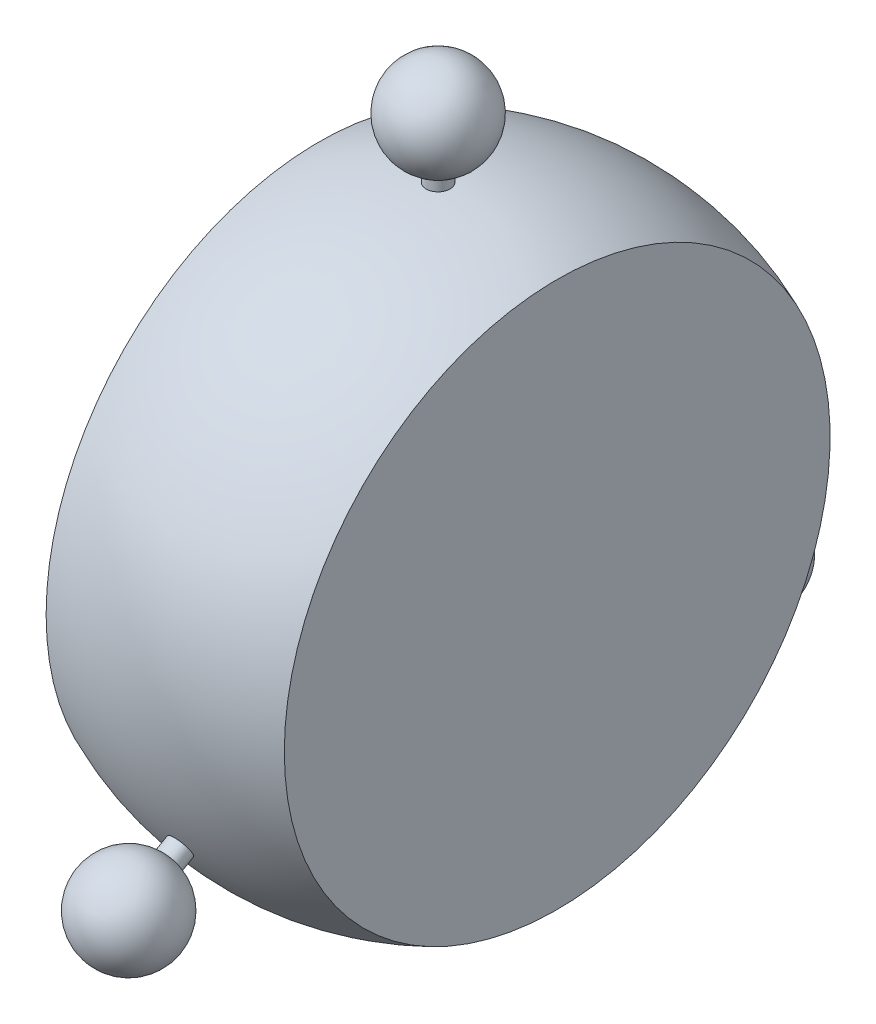
SolidWorks part; units mm, degrees
ref_plane "Alzado" through (0, 0, 0) normal (0, 0, 1) x (1, 0, 0)
ref_plane "Planta" through (0, 0, 0) normal (0, 1, 0) x (1, 0, 0)
ref_plane "Vista lateral" through (0, 0, 0) normal (1, 0, 0) x (0, 0, -1)
sketch "Croquis1" plane through (0, 0, 0) normal (0, 0, 1) x (1, 0, 0)
  line L0 (0, -25) -> (0, -20)
  line L1 (0, 20) -> (0, 25)
  line L2 (0, 0) -> (0, 16.1824) construction
  arc A0 (0, -20) -> (0, 20) centre (0, 0) ccw
  arc A1 (0, -25) -> (0, 25) centre (0, 0) ccw
  dimension "D1" = 20
  dimension "D2" = 25
sketch "Croquis2" plane through (0, 0, 0) normal (0, 1, 0) x (1, 0, 0)
  line L15 (-10, -25) -> (-28.0856, -25)
  line L16 (-10, -25) -> (-10, 25)
  line L17 (-10, 25) -> (-28.0856, 25)
  line L18 (-28.0856, -25) -> (-28.0856, 25)
  line L19 (10, -25) -> (27.1051, -25)
  line L20 (10, -25) -> (10, 25)
  line L21 (10, 25) -> (27.1051, 25)
  line L22 (27.1051, -25) -> (27.1051, 25)
  point P0 (0, 0)
  point P10 (0, 0)
  dimension "D1" = 50
  dimension "D2" = 20
sketch "Croquis3" plane through (0, 0, 0) normal (1, 0, 0) x (0, 0, -1)
  line L0 (0, 25) -> (0, 34)
  line L4 (1, 26.127) -> (1, 24.98)
  arc A0 (1, 24.98) -> (0, 25) centre (0, 0) ccw
  arc A1 (1, 26.127) -> (0, 34) centre (0, 30) ccw
  point P3 (0, 25)
  point P4 (0, 25)
  point P5 (0, 9.4331)
  dimension "D1" = 4
  dimension "D2" = 1.147
sketch "Croquis5" plane through (0, 0, 0) normal (0, 0, 1) x (1, 0, 0)
  line L0 (0, 0) -> (74.6384, 0) construction
sketch "Croquis8" plane through (0, 0, 0) normal (0, 0, 1) x (1, 0, 0)
  line L0 (-10, 22.9129) -> (-10, 17.3205)
  line L3 (10, 22.9129) -> (10, 0)
  line L5 (0, 0) -> (10, 0)
  arc A1 (10, 22.9129) -> (-10, 22.9129) centre (0, 0) ccw
  arc A2 (-10, 17.3205) -> (0, 0) centre (-20, 0) cw
revolve "Revolución4" add sketch "Croquis8" angle 360 about L0
revolve "Revolución5" add sketch "Croquis3" angle 360 about L0
pattern_circular "MatrizC1" count 3 over 360 about axis through (0, 0, 0) along (1, 0, 0) of "Revolución5", "Revolución4"
